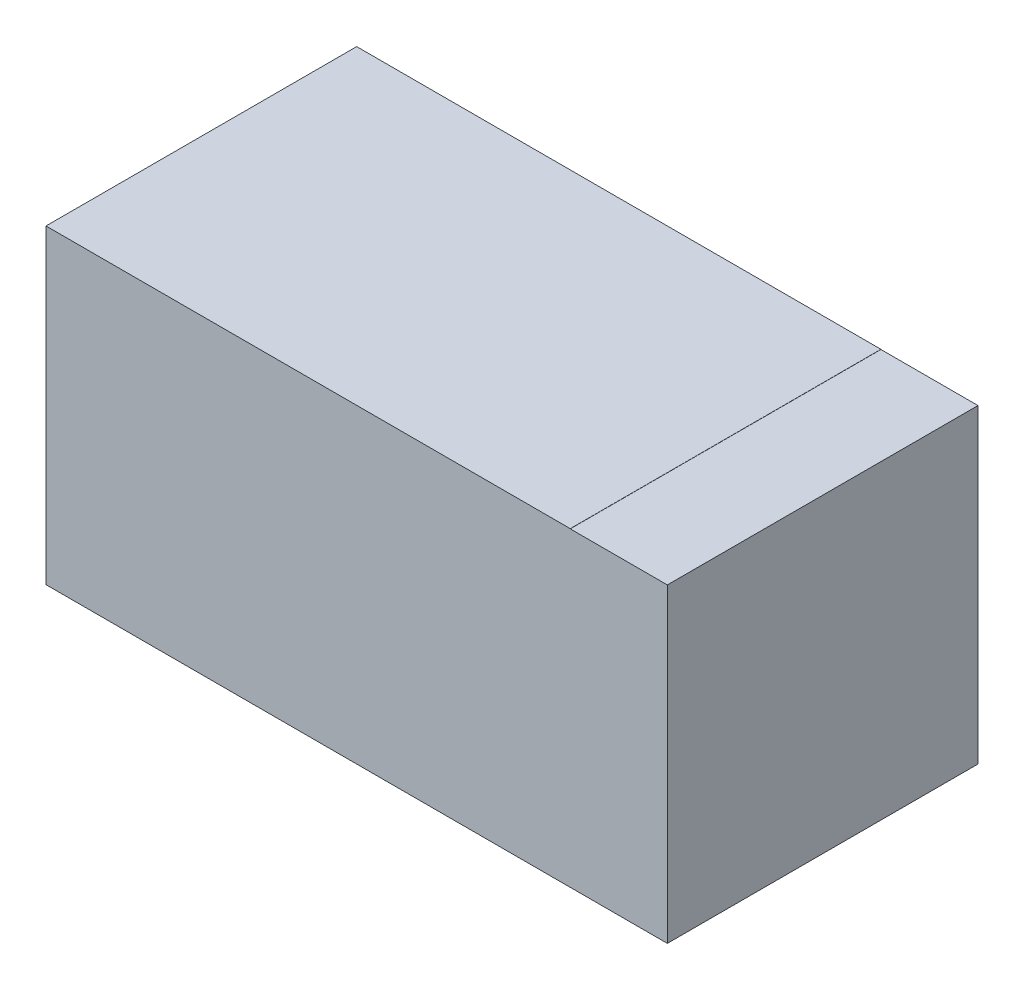
SolidWorks part; units mm, degrees
ref_plane "Front Plane" through (0, 0, 0) normal (0, 0, 1) x (1, 0, 0)
ref_plane "Top Plane" through (0, 0, 0) normal (0, 1, 0) x (1, 0, 0)
ref_plane "Right Plane" through (0, 0, 0) normal (1, 0, 0) x (0, 0, -1)
sketch "Sketch1" plane through (0, 0, 0) normal (0, 1, 0) x (1, 0, 0)
  line L1 (1.6, 0.8) -> (-1.6, 0.8)
  line L2 (1.6, 0.8) -> (1.6, -0.8)
  line L3 (1.6, -0.8) -> (-1.6, -0.8)
  line L4 (-1.6, 0.8) -> (-1.6, -0.8)
  line L5 (1.6, 0.8) -> (-1.6, -0.8) construction
  line L6 (1.6, -0.8) -> (-1.6, 0.8) construction
  point P0 (0, 0)
  dimension "D1" = 3.2
  dimension "D2" = 1.6
extrude "Boss-Extrude1" add sketch "Sketch1" along normal blind 1.6
sketch "Sketch2" plane through (0, 1.6, 0) normal (0, 1, 0) x (1, 0, 0)
  line L0 (-1.6, -0.8) -> (1.6, -0.8) construction
  line L1 (1.6, 0.8) -> (1.1, 0.8)
  line L2 (1.6, 0.8) -> (1.6, -0.8)
  line L3 (1.6, -0.8) -> (1.1, -0.8)
  line L4 (1.1, 0.8) -> (1.1, -0.8)
  dimension "D1" = 0.5
extrude "Cut-Extrude1" cut sketch "Sketch2" against normal blind 0.001
